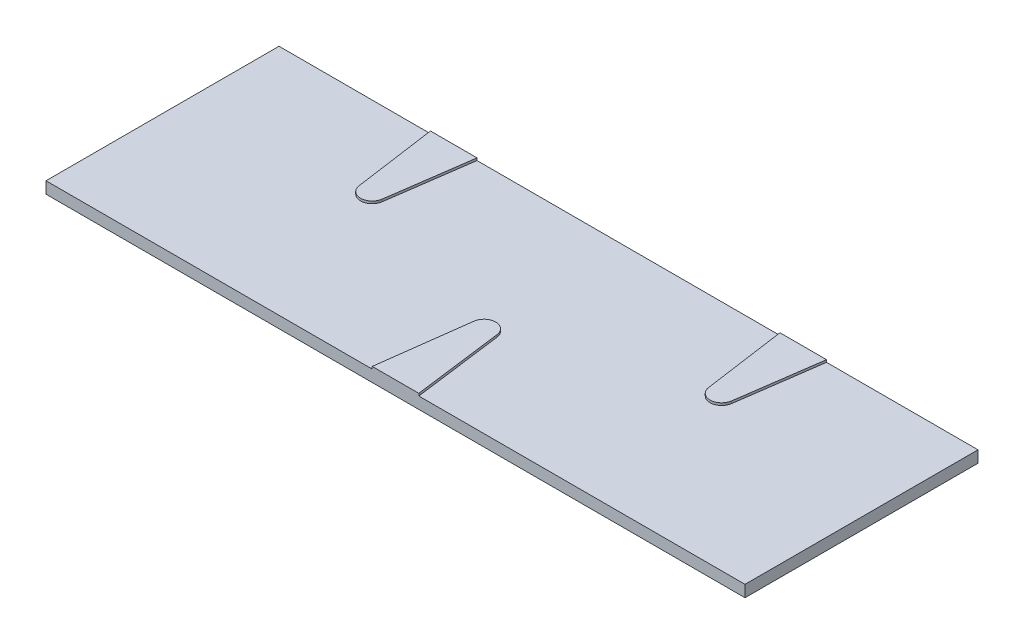
SolidWorks part; units mm, degrees
ref_plane "Front Plane" through (0, 0, 0) normal (0, 0, 1) x (1, 0, 0)
ref_plane "Top Plane" through (0, 0, 0) normal (0, 1, 0) x (1, 0, 0)
ref_plane "Right Plane" through (0, 0, 0) normal (1, 0, 0) x (0, 0, -1)
sketch "Sketch1" plane through (0, 0, 0) normal (0, 1, 0) x (1, 0, 0)
  line L1 (-150, -50) -> (150, -50)
  line L2 (-150, -50) -> (-150, 50)
  line L3 (-150, 50) -> (150, 50)
  line L4 (150, -50) -> (150, 50)
  line L5 (-150, -50) -> (150, 50) construction
  line L6 (-150, 50) -> (150, -50) construction
  point P0 (0, 0)
  dimension "D1" = 300
  dimension "D2" = 100
extrude "Boss-Extrude1" add sketch "Sketch1" along normal blind 5
sketch "Sketch2" plane through (0, 5, 0) normal (0, 1, 0) x (1, 0, 0)
  line L0 (-85, 50) -> (-79.9507, 14.2998)
  line L1 (150, 50) -> (-150, 50) construction
  line L2 (-70.0493, 14.2998) -> (-65, 50)
  line L3 (0, 0) -> (0, 70.5227) construction
  line L4 (-75, 15) -> (-75, 39.2884) construction
  line L5 (70.0493, 14.2998) -> (65, 50)
  line L6 (85, 50) -> (79.9507, 14.2998)
  line L7 (65, 50) -> (85, 50)
  line L8 (-85, 50) -> (-65, 50)
  line L9 (4.958, -11.3532) -> (10, -50)
  line L10 (-10, -50) -> (-4.958, -11.3532)
  line L11 (10, -50) -> (-10, -50)
  line L12 (-150, -50) -> (150, -50) construction
  arc A0 (-79.9507, 14.2998) -> (-70.0493, 14.2998) centre (-75, 15) ccw
  arc A1 (79.9507, 14.2998) -> (70.0493, 14.2998) centre (75, 15) cw
  arc A2 (-4.958, -11.3532) -> (4.958, -11.3532) centre (0, -12) cw
  point P21 (0, 0)
  point P24 (0, 0)
  dimension "D2" = 5
  dimension "D5" = 5
  dimension "D1" = 35
  dimension "D3" = 20
  dimension "D4" = 65
  dimension "D6" = 38
  dimension "D7" = 20
extrude "Boss-Extrude2" add sketch "Sketch2" along normal blind 1
